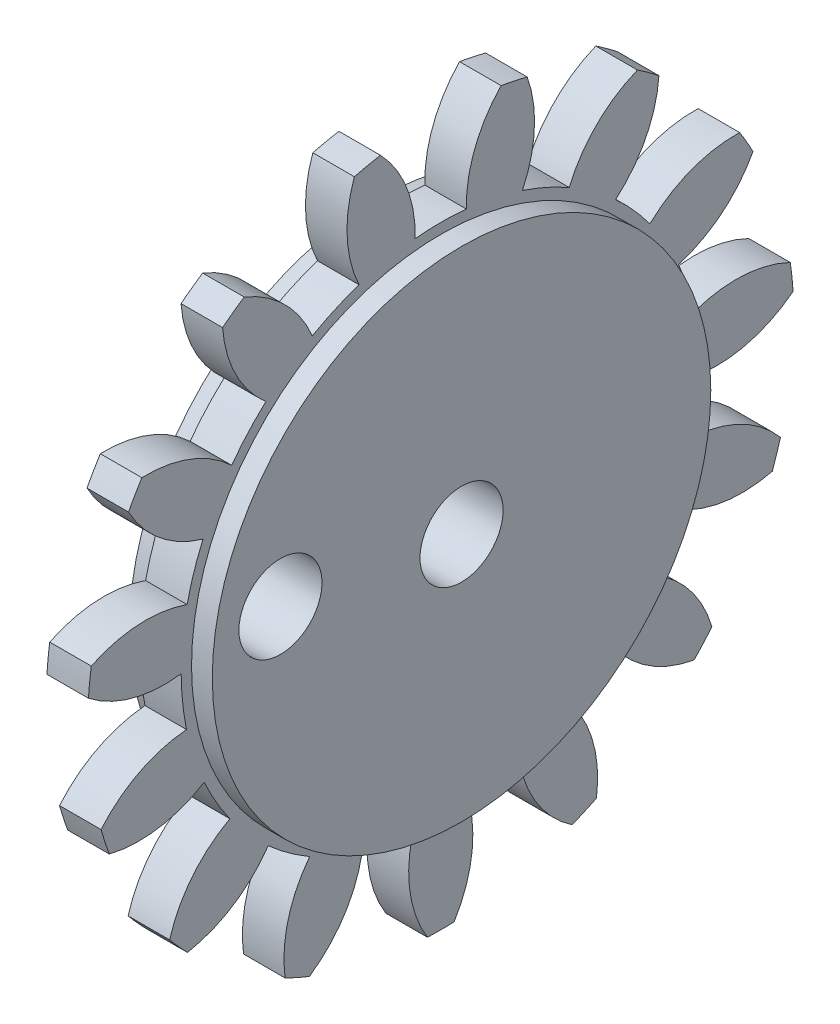
SolidWorks part; units mm, degrees
ref_plane "Plane1" through (0, 0, 0) normal (0, 0, 1) x (1, 0, 0)
ref_plane "Plane2" through (0, 0, 0) normal (0, 1, 0) x (1, 0, 0)
ref_plane "Plane3" through (0, 0, 0) normal (1, 0, 0) x (0, 0, -1)
other "Configuration Table"
sketch "HoldingSke" plane through (0, 0, 0) normal (0, 1, 0) x (1, 0, 0)
  line L0 (0, 0) -> (98.1381, -26.296)
  line L1 (-15, 0) -> (100, 0) construction
  line L2 (0, 0) -> (-2.1039, 2.3779)
  line L3 (0, 0) -> (-11.863, 4.5341)
  line L4 (0, 0) -> (8.3417, 2.2352)
  line L5 (0, 0) -> (-11.8993, -4.4381)
  line L6 (0, 0) -> (-5.2639, -3.5516)
  line L7 (-2.1039, 2.3779) -> (0.6298, 14.7802)
  line L8 (-76.2, 54.61) -> (-61.976, 54.61)
  line L9 (-67.7845, 28.3722) -> (-49.3413, 33.142)
  line L10 (-76.2, 71.12) -> (104.1128, 71.12)
  line L11 (0, 0) -> (-6.35, 0)
  line L12 (-76.2, 101.6) -> (-75.9714, 101.6)
  line L13 (24.9733, 27.94) -> (52.9518, 28.4284)
  line L14 (24.9733, 27.94) -> (24.9746, 27.94)
  line L15 (24.9733, 27.94) -> (100.4006, 29.5858)
  circle A0 centre (0, 0) radius 6.35
  circle A1 centre (0, 0) radius 38.1
  circle A2 centre (0, 0) radius 38.1
  circle A3 centre (0, 0) radius 6.35
  dimension "MHD" = 76.2
  dimension "Hub_dia" = 76.2
  dimension "Bore" = 12.7
  dimension "MBD" = 12.7
  dimension "Num_teeth" = 15
  dimension "Pitch" = 101.6
  dimension "Overall_len" = 12.7
  dimension "Show_teeth" = 15
  dimension "Thickness" = 6.35
  dimension "OAL" = 12.7001
  dimension "T_dim" = 14.224
  dimension "Ap" = 14.5
  dimension "H" = 19.05
  dimension "Pitch_radius" = 180.3128
  dimension "Width" = 6.35
  dimension "Backlash" = 0.2286
  dimension "Addendum_fac" = 1
  dimension "Dedendum_fac" = 1.25
  dimension "Clearance_fac" = 0.25
  dimension "Dedendum_add" = 0.0013
sketch "BasProSke" plane through (0, 0, 0) normal (0, 1, 0) x (1, 0, 0)
  line L0 (-10, 0) -> (60, 0) construction
  line L1 (0, 0) -> (0, 53.975)
  line L2 (0, 0) -> (6.35, 0)
  line L3 (6.35, 0) -> (6.35, 53.975)
  line L4 (6.35, 53.975) -> (0, 53.975)
  dimension "Thickness" = 6.35
  dimension "Diameter" = 107.95
revolve "Base-Revolve" add sketch "BasProSke" angle 360 about L0
sketch "TooCutSke" plane through (0, 0, 0) normal (1, 0, 0) x (0, 0, -1)
  line L1 (0, 0) -> (0, 107) construction
  line L2 (0, 0) -> (-5.3779, 47.3204) construction
  line L3 (0, 0) -> (-19.7119, 92.7371) construction
  line L4 (-5.3779, 47.3204) -> (-9.8559, 46.3685) construction
  arc A0 (3.9155, 39.4926) -> (-3.9155, 39.4926) centre (0, 0) ccw
  arc A1 (9.2414, 53.2038) -> (-9.2414, 53.2038) centre (0, 0) ccw
  circle A2 centre (0, 0) radius 47.625 construction
  circle A3 centre (0, 0) radius 46.108 construction
  arc A4 (-3.9155, 39.4926) -> (-9.2414, 53.2038) centre (-22.9591, 39.9854) ccw
  arc A5 (9.2414, 53.2038) -> (3.9155, 39.4926) centre (22.9591, 39.9854) ccw
  dimension "Root_dia" = 79.3725
  dimension "Overcut_dia" = 108.0008
  dimension "Pitch_dia" = 95.25
  dimension "Base_dia" = 92.2161
  dimension "Flank_rad" = 19.05
  dimension "Half_ang" = 12
  dimension "Half_CT" = 4.5781
extrude "ToothCut" cut sketch "TooCutSke" along normal through all
fillet "Breaks" [suppressed] radius 0.127
fillet "RootFillets" [suppressed] radius 1.5888
pattern_circular "TeethCuts" count 15 every 24 about axis through (-10, 0, 0) along (1, 0, 0) of "ToothCut", "RootFillets", "Breaks"
sketch "HubNeaOneSke" plane through (0, 0, 0) normal (-1, 0, 0) x (0, 0, 1)
  circle A0 centre (0, 0) radius 38.1
  dimension "Diameter" = 76.2
extrude "HubNearOne" [suppressed] add sketch "HubNeaOneSke" along normal blind 6.3501
sketch "HubNeaBotSke" plane through (0, 0, 0) normal (-1, 0, 0) x (0, 0, 1)
  circle A0 centre (0, 0) radius 38.1
  dimension "Diameter" = 76.2
extrude "HubNearBoth" add sketch "HubNeaBotSke" along normal blind 3.175
ref_plane "FarPln" through (6.35, 0, 0) normal (1, 0, 0) x (0, 0, -1)
sketch "HubFarSke" plane through (6.35, 0, 0) normal (1, 0, 0) x (0, 0, -1)
  circle A0 centre (0, 0) radius 38.1
  dimension "Diameter" = 76.2
extrude "HubFar" add sketch "HubFarSke" along normal blind 3.175
sketch "BorSke" plane through (0, 0, 0) normal (1, 0, 0) x (0, 0, -1)
  circle A0 centre (0, 0) radius 6.35
  dimension "Diameter" = 12.7
extrude "Bore" cut sketch "BorSke" along normal mid plane 25.4001
sketch "KeySke" plane through (0, 0, 0) normal (1, 0, 0) x (0, 0, -1)
  line L0 (-1.5875, 0) -> (-1.5875, 7.874)
  line L1 (-1.5875, 7.874) -> (1.5875, 7.874)
  line L2 (1.5875, 7.874) -> (1.5875, 0)
  line L3 (0, 0) -> (0, 34) construction
  line L4 (-1.5875, 0) -> (1.5875, 0)
  dimension "Offset" = 7.874
  dimension "Width" = 3.175
extrude "Keyway" [suppressed] cut sketch "KeySke" along normal mid plane 25.4001
pattern_circular "Keyway2" [suppressed] count 2 every 90 about axis through (-10, 0, 0) along (1, 0, 0)
sketch "Sketch1" plane through (-3.175, 0, 0) normal (-1, 0, 0) x (0, 0, 1)
  line L0 (0, 0) -> (27.6826, 4.2691) construction
  line L1 (0, 0) -> (46.7437, 26.9875) construction
  circle A0 centre (27.6826, 4.2691) radius 6.35
  arc A1 (47.7296, 25.2029) -> (45.6911, 28.7336) centre (0, 0) ccw construction
  circle A2 centre (0, 0) radius 28.0098 construction
  circle A3 centre (24.2572, 14.0049) radius 6.35 construction
  dimension "D1" = 12.7
extrude "Cut-Extrude1" cut sketch "Sketch1" against normal through all
scale "Scale1" bodies to scale 108 scale about centroid uniform scaling yes scale factor 0.75
equation "' \"Pitch@HoldingSke\" = 4"
equation "' \"Num_teeth@HoldingSke\" = 12"
equation "' \"Ap@HoldingSke\" =  20"
equation "' \"Ap@HoldingSke\" = 20"
equation "' \"Width@HoldingSke\" = 0.5"
equation "' \"Hub_dia@HoldingSke\"= 1"
equation "' \"Hub_dia@HoldingSke\" = 1"
equation "' \"Overall_len@HoldingSke\" = 1.0"
equation "' \"Bore@HoldingSke\" = 0.75"
equation "' \"T_dim@HoldingSke\" = 0.85"
equation "' \"Width@KeySke\" = 0.25"
equation "' \"Show_teeth@HoldingSke\" = 13"
equation "' \"Backlash@HoldingSke\" = 0.009"
equation "' \"Addendum_fac@HoldingSke\" = 1.0"
equation "' \"Dedendum_fac@HoldingSke\" = 1.25"
equation "' \"Dedendum_add@HoldingSke\" = 0.00005"
equation "' \"Clearance_fac@HoldingSke\" = 0.25"
equation "' \"Pitch@HoldingSke\" = 0.5"
equation "' \"Num_teeth@HoldingSke\" = 23"
equation "' \"Show_teeth@HoldingSke\" = 23"
equation "' \"Backlash@HoldingSke\" = 0.0375"
equation "\"Overcut_dia@TooCutSke\" = (\"Num_teeth@HoldingSke\" + 2 * \"Addendum_fac@HoldingSke\") / \"Pitch@HoldingSke\" + 0.002"
equation "\"Pitch_dia@TooCutSke\" = \"Num_teeth@HoldingSke\" / \"Pitch@HoldingSke\""
equation "\"Base_dia@TooCutSke\" = \"Num_teeth@HoldingSke\" / \"Pitch@HoldingSke\" * cos((\"Ap@HoldingSke\"  * 3.14159265 / 180))"
equation "\"Root_dia@TooCutSke\" = (\"Num_teeth@HoldingSke\" + 2) / \"Pitch@HoldingSke\" - 2 * (\"Addendum_fac@HoldingSke\" + \"Dedendum_fac@HoldingSke\") / \"Pitch@HoldingSke\" - \"Dedendum_add@HoldingSke\" * 2"
equation "\"Half_ang@TooCutSke\" = 180 / \"Num_teeth@HoldingSke\""
equation "\"Half_CT@TooCutSke\" = \"Num_teeth@HoldingSke\" / \"Pitch@HoldingSke\" * sin((3.14159265 / 2 / \"Num_teeth@HoldingSke\")) / 2 - 7 * \"Backlash@HoldingSke\" / 4"
equation "\"Flank_rad@TooCutSke\" = \"Num_teeth@HoldingSke\" / \"Pitch@HoldingSke\" / 5"
equation "\"Radius@RootFillets\" = \"Clearance_fac@HoldingSke\" / \"Pitch@HoldingSke\" + \"Dedendum_add@HoldingSke\""
equation "\"Break_rad@Breaks\" = 0.02 / \"Pitch@HoldingSke\""
equation "\"Thickness@HoldingSke\" = \"Width@HoldingSke\""
equation "\"OAL@HoldingSke\" = \"Thickness@HoldingSke\""
equation "\"MHD@HoldingSke\" = (\"Num_teeth@HoldingSke\" + 2) / \"Pitch@HoldingSke\" - 2 * (\"Addendum_fac@HoldingSke\" + \"Dedendum_fac@HoldingSke\")  / \"Pitch@HoldingSke\" - \"Dedendum_add@HoldingSke\" * 2"
equation "\"MBD@HoldingSke\" = (\"Num_teeth@HoldingSke\" + 2) / \"Pitch@HoldingSke\" - 2 * (\"Addendum_fac@HoldingSke\" + \"Dedendum_fac@HoldingSke\")  / \"Pitch@HoldingSke\" - \"Dedendum_add@HoldingSke\" * 2 - 0.002"
equation "\"MHD@HoldingSke\" = ((sgn( \"MHD@HoldingSke\" - \"Hub_dia@HoldingSke\" )-1)*( \"MHD@HoldingSke\" - \"Hub_dia@HoldingSke\" ))/-2+ \"Hub_dia@HoldingSke\""
equation "\"MBD@HoldingSke\" = ((sgn( \"MBD@HoldingSke\" - \"Bore@HoldingSke\" )-1)*( \"MBD@HoldingSke\" - \"Bore@HoldingSke\" ))/-2+ \"Bore@HoldingSke\""
equation "\"OAL@HoldingSke\" = ((sgn( \"OAL@HoldingSke\" - \"Overall_len@HoldingSke\" )+1)*( \"OAL@HoldingSke\" - \"Overall_len@HoldingSke\" ))/2 + \"Overall_len@HoldingSke\" + 0.000002"
equation "\"Num_teeth@TeethCuts\" = int( \"Show_teeth@HoldingSke\" ) + 1"
equation "\"Num_teeth@TeethCuts\" = ((sgn( \"Num_teeth@TeethCuts\" - \"Num_teeth@HoldingSke\" )-1)*( \"Num_teeth@TeethCuts\" - \"Num_teeth@HoldingSke\" ))/-2+ \"Num_teeth@HoldingSke\""
equation "\"Num_teeth@TeethCuts\" = ((sgn( \"Num_teeth@TeethCuts\" - 2.0)+1)*( \"Num_teeth@TeethCuts\" - 2.0))/2 +2.0"
equation "\"Angle@TeethCuts\" = 360.0 / \"Num_teeth@HoldingSke\""
equation "\"Diameter@BasProSke\" = (\"Num_teeth@HoldingSke\" + 2 * \"Addendum_fac@HoldingSke\") / \"Pitch@HoldingSke\""
equation "\"Thickness@BasProSke\"  = \"Thickness@HoldingSke\""
equation "' \"Fillet_rad@BasProSke\" =  \"Thickness@HoldingSke\" * 0.05"
equation "' \"Fillet_rad@BasProSke\" = \"Thickness@HoldingSke\" * 0.05"
equation "\"MHD@HoldingSke\" = ((sgn( \"MHD@HoldingSke\" - \"Root_dia@TooCutSke\" )-1)*( \"MHD@HoldingSke\" - \"Root_dia@TooCutSke\" ))/-2+ \"Root_dia@TooCutSke\""
equation "\"Diameter@HubNeaOneSke\" = \"MHD@HoldingSke\""
equation "\"Length@HubNearOne\" = \"OAL@HoldingSke\" - \"Thickness@BasProSke\""
equation "\"Diameter@HubNeaBotSke\" = \"MHD@HoldingSke\""
equation "\"Length@HubNearBoth\" = ( \"OAL@HoldingSke\" - \"Thickness@BasProSke\" ) / 2.0"
equation "\"Thickness@FarPln\" = \"Thickness@BasProSke\""
equation "\"Diameter@HubFarSke\" = \"MHD@HoldingSke\""
equation "\"Length@HubFar\" = ( \"OAL@HoldingSke\" - \"Thickness@BasProSke\" ) / 2.0"
equation "\"Diameter@BorSke\" = \"MBD@HoldingSke\""
equation "\"D1@Bore\" = \"OAL@HoldingSke\" * 2.0"
equation "\"D1@Keyway\" = \"OAL@HoldingSke\" * 2.0"
equation "\"Offset@KeySke\" = \"T_dim@HoldingSke\" - \"MBD@HoldingSke\" / 2.0"
